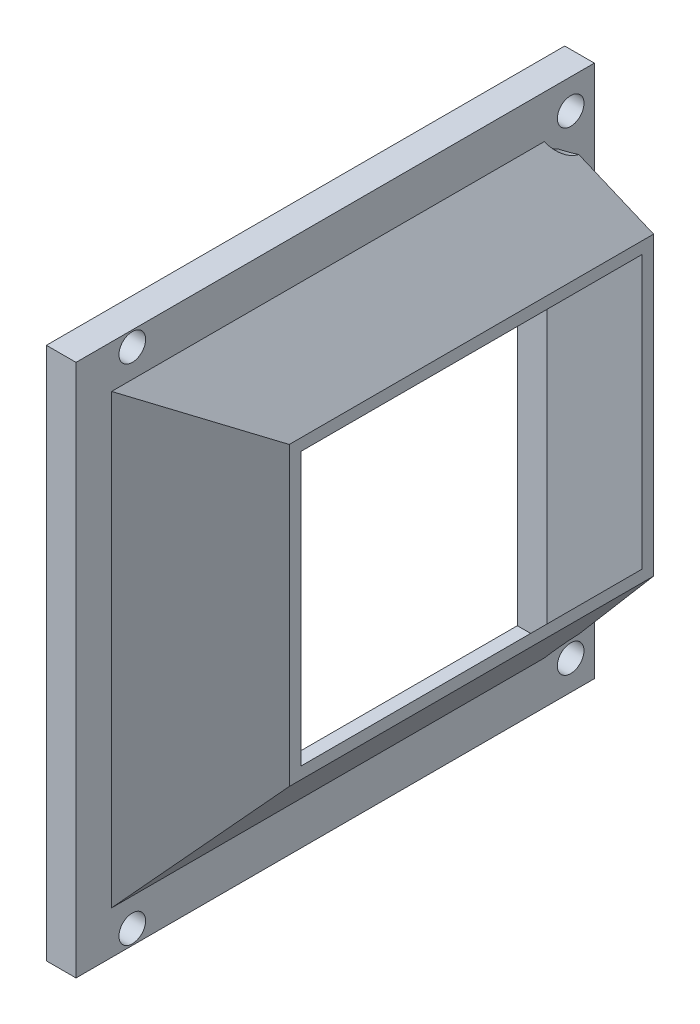
SolidWorks part; units mm, degrees
ref_plane "Front Plane" through (0, 0, 0) normal (0, 0, 1) x (1, 0, 0)
ref_plane "Top Plane" through (0, 0, 0) normal (0, 1, 0) x (1, 0, 0)
ref_plane "Right Plane" through (0, 0, 0) normal (1, 0, 0) x (0, 0, -1)
sketch "Sketch1" plane through (0, 0, 0) normal (1, 0, 0) x (0, 0, -1)
  line L1 (-43.75, -45) -> (43.75, -45)
  line L2 (-43.75, -45) -> (-43.75, 45)
  line L3 (-43.75, 45) -> (43.75, 45)
  line L4 (43.75, -45) -> (43.75, 45)
  line L5 (-43.75, -45) -> (43.75, 45) construction
  line L6 (-43.75, 45) -> (43.75, -45) construction
  line L7 (-35.75, -35.75) -> (35.75, -35.75)
  line L8 (-35.75, -35.75) -> (-35.75, 35.75)
  line L9 (-35.75, 35.75) -> (35.75, 35.75)
  line L10 (35.75, -35.75) -> (35.75, 35.75)
  line L11 (-35.75, -35.75) -> (35.75, 35.75) construction
  line L12 (-35.75, 35.75) -> (35.75, -35.75) construction
  point P0 (0, 0)
  point P6 (0, 0)
  dimension "D1" = 87.5
  dimension "D2" = 90
  dimension "D3" = 71.5
  dimension "D4" = 71.5
extrude "Boss-Extrude1" add sketch "Sketch1" along normal blind 5
hole_wizard "M4 Clearance Hole1" positions "Sketch2" profile "Sketch3" hole size "M4" standard "ANSI Metric" end condition through all
sketch "Sketch2" plane through (5, 0, 0) normal (1, 0, 0) x (0, 0, -1)
  line L0 (43.75, -45) -> (43.75, 45) construction
  line L1 (43.75, 45) -> (-43.75, 45) construction
  line L2 (-43.75, 45) -> (-43.75, -45) construction
  point P0 (-34.25, 42.5)
  point P2 (39.75, 40)
  dimension "D1" = 4
  dimension "D2" = 5
  dimension "D3" = 9.5
  dimension "D4" = 2.5
sketch "Sketch3" plane through (5, 42.5, 34.25) normal (0, 1, 0) x (0, 0, -1)
  line L0 (0, 0) -> (0, 5)
  line L1 (0, 5) -> (2.25, 5)
  line L2 (2.25, 5) -> (2.25, 0)
  line L5 (2.25, 0) -> (0, 0)
  line L11 (0, -6.35) -> (0, 107.95) construction
  dimension "Thru Hole Dia." = 4.5
  dimension "Thru Hole Depth" = 5
mirror "Mirror1" about plane through (0, 0, 0) normal (0, 1, 0) of "M4 Clearance Hole1"
sketch "Sketch4" plane through (0, 45, 0) normal (0, 1, 0) x (1, 0, 0)
  line L0 (5, 35.75) -> (15, 41.75)
  line L1 (5, 43.75) -> (5, -43.75) construction
  line L2 (5, -35.75) -> (15, -15.75)
  line L4 (15, -15.75) -> (15, -17.75)
  line L5 (15, -17.75) -> (5, -37.75)
  line L6 (15, 41.75) -> (15, 43.75)
  line L7 (15, 43.75) -> (5, 37.75)
  line L8 (5, -37.75) -> (5, -35.75)
  line L9 (5, 35.75) -> (5, 37.75)
  dimension "D1" = 20
  dimension "D2" = 10
  dimension "D3" = 10
  dimension "D4" = 2
  dimension "D5" = 2
  dimension "D6" = 8
  dimension "D7" = 8
extrude "Boss-Extrude2" add sketch "Sketch4" against normal up to vertex (90 mm away) up to point (5, -45, 43.75)
sketch "Sketch5" plane through (0, 0, -43.75) normal (0, 0, -1) x (-1, 0, 0)
  line L0 (-5, 35.75) -> (-15, 23)
  line L1 (-5, -45) -> (-5, 45) construction
  line L2 (-15, 23) -> (-15, 25)
  line L3 (-15, 25) -> (-5, 37.75)
  line L4 (-5, 45) -> (0, 45) construction
  line L5 (-5, -37.75) -> (-15, -25)
  line L6 (-15, -25) -> (-15, -23)
  line L7 (-15, -23) -> (-5, -35.75)
  line L8 (-5, 37.75) -> (-5, 35.75)
  line L9 (-5, -35.75) -> (-5, -37.75)
  dimension "D1" = 2
  dimension "D2" = 10
  dimension "D3" = 20
  dimension "D4" = 9.25
  dimension "D5" = 2
  dimension "D6" = 10
  dimension "D7" = 20
  dimension "D8" = 9.25
extrude "Boss-Extrude3" add sketch "Sketch5" against normal up to vertex (87.5 mm away) up to point (0, -45, 43.75)
sketch "Sketch6" plane through (0, 0, -43.75) normal (0, 0, -1) x (-1, 0, 0)
  line L0 (-5, 45) -> (-15, 45)
  line L1 (-15, 45) -> (-15, 25)
  line L2 (-15, 25) -> (-5, 37.75)
  line L3 (-5, 37.75) -> (-5, 45)
  line L4 (-15, -25) -> (-15, -45)
  line L5 (-15, -45) -> (-5, -45)
  line L6 (-5, -45) -> (-5, -37.75)
  line L7 (-5, -37.75) -> (-15, -25)
extrude "Cut-Extrude1" cut sketch "Sketch6" against normal up to vertex
sketch "Sketch7" plane through (0, 45, 0) normal (0, 1, 0) x (1, 0, 0)
  line L0 (5, -43.75) -> (15, -43.75)
  line L2 (15, -43.75) -> (15, -17.75)
  line L3 (5, -43.75) -> (5, -37.75)
  line L4 (5, 43.75) -> (5, -43.75) construction
  line L5 (5, -37.75) -> (15, -17.75)
  line L6 (5, 43.75) -> (15, 43.75)
  line L7 (15, 43.75) -> (5, 37.75)
  line L8 (5, 43.75) -> (5, 37.75)
  dimension "D1" = 26
  dimension "D2" = 10
  dimension "D3" = 6
  dimension "D4" = 10
  dimension "D5" = 6
extrude "Cut-Extrude2" cut sketch "Sketch7" against normal up to vertex
sketch "Sketch8" plane through (5, 0, 0) normal (1, 0, 0) x (0, 0, -1)
  circle A0 centre (39.75, 40) radius 5
  circle A1 centre (39.75, -40) radius 5
  dimension "D1" = 10
  dimension "D2" = 10
extrude "Cut-Extrude3" cut sketch "Sketch8" along normal blind 10
